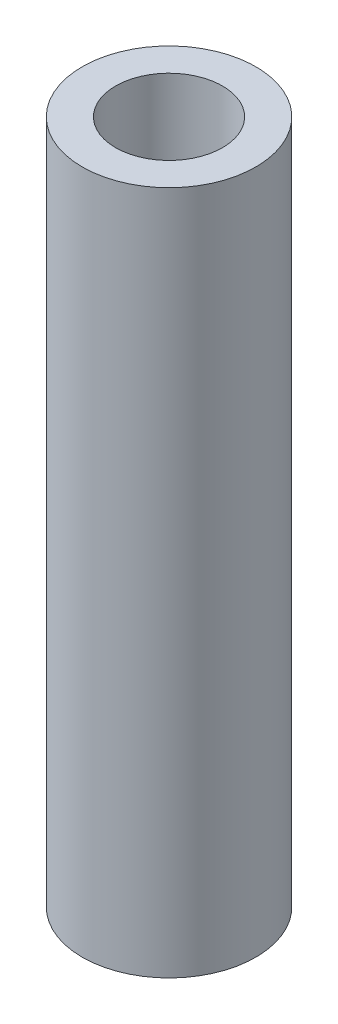
SolidWorks part; units mm, degrees
ref_plane "Front Plane" through (0, 0, 0) normal (0, 0, 1) x (1, 0, 0)
ref_plane "Top Plane" through (0, 0, 0) normal (0, 1, 0) x (1, 0, 0)
ref_plane "Right Plane" through (0, 0, 0) normal (1, 0, 0) x (0, 0, -1)
sketch "Sketch1" plane through (0, 0, 0) normal (0, 1, 0) x (1, 0, 0)
  circle A0 centre (0, 0) radius 1.5875
  circle A1 centre (0, 0) radius 2.5778
  dimension "D1" = 3.175
extrude "Boss-Extrude1" add sketch "Sketch1" along normal blind 20.32
